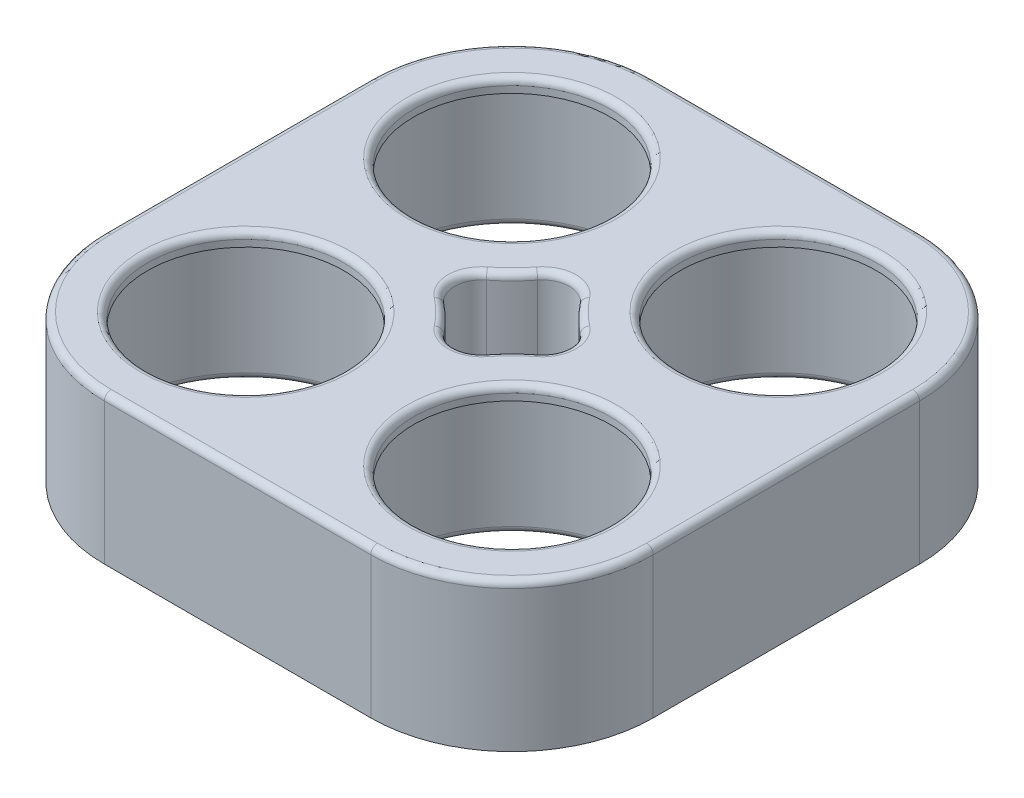
SolidWorks part; units mm, degrees
ref_plane "Front Plane" through (0, 0, 0) normal (0, 0, 1) x (1, 0, 0)
ref_plane "Top Plane" through (0, 0, 0) normal (0, 1, 0) x (1, 0, 0)
ref_plane "Right Plane" through (0, 0, 0) normal (1, 0, 0) x (0, 0, -1)
sketch "Esquisse1" plane through (0, 0, 0) normal (0, 1, 0) x (1, 0, 0)
  line L0 (0, 0) -> (19.8, 0) construction
  line L1 (0, 0) -> (0, 19.8) construction
  line L2 (19.8, 0) -> (19.8, 19.8) construction
  line L3 (-10.5, 19.8) -> (-10.5, 0)
  line L4 (0, 30.3) -> (19.8, 30.3)
  line L5 (30.3, 19.8) -> (30.3, 0)
  line L6 (0, -10.5) -> (19.8, -10.5)
  circle A0 centre (0, 0) radius 9.3
  arc A1 (-10.5, 0) -> (0, -10.5) centre (0, 0) ccw
  circle A2 centre (0, 19.8) radius 9.3
  arc A3 (6.4105, 11.484) -> (8.316, 13.3895) centre (0, 19.8) ccw
  circle A4 centre (19.8, 0) radius 9.3
  arc A5 (13.3895, 8.316) -> (11.484, 6.4105) centre (19.8, 0) ccw
  circle A6 centre (19.8, 19.8) radius 9.3
  arc A7 (30.3, 19.8) -> (19.8, 30.3) centre (19.8, 19.8) ccw
  arc A8 (0, 30.3) -> (-10.5, 19.8) centre (0, 19.8) ccw
  arc A9 (11.484, 13.3895) -> (13.3895, 11.484) centre (19.8, 19.8) ccw
  arc A10 (8.316, 6.4105) -> (6.4105, 8.316) centre (0, 0) ccw
  arc A11 (19.8, -10.5) -> (30.3, 0) centre (19.8, 0) ccw
  arc A12 (6.4105, 11.484) -> (6.4105, 8.316) centre (7.6315, 9.9) ccw
  arc A13 (8.316, 13.3895) -> (11.484, 13.3895) centre (9.9, 12.1685) cw
  arc A14 (13.3895, 11.484) -> (13.3895, 8.316) centre (12.1685, 9.9) cw
  arc A15 (8.316, 6.4105) -> (11.484, 6.4105) centre (9.9, 7.6315) ccw
  dimension "D1" = 18.6
  dimension "D2" = 18.6
  dimension "D3" = 18.6
  dimension "D4" = 18.6
  dimension "D5" = 1.2
  dimension "D6" = 1.2
  dimension "D7" = 1.2
  dimension "D8" = 1.2
  dimension "D9" = 2
extrude "Boss.-Extru.1" add sketch "Esquisse1" along normal blind 10
sketch "Esquisse2" plane through (0, 10, 0) normal (0, 1, 0) x (1, 0, 0)
  line L148 (-10.5, 19.8) -> (-10.5, 0)
  line L149 (0, -10.5) -> (19.8, -10.5)
  line L150 (30.3, 0) -> (30.3, 19.8)
  line L151 (19.8, 30.3) -> (0, 30.3)
  line L152 (-10.5, 19.8) -> (-10.5, 0)
  line L153 (0, -10.5) -> (19.8, -10.5)
  line L154 (30.3, 0) -> (30.3, 19.8)
  line L155 (19.8, 30.3) -> (0, 30.3)
  circle A403 centre (0, 19.8) radius 7.3
  circle A404 centre (19.8, 19.8) radius 7.3
  circle A405 centre (19.8, 0) radius 7.3
  circle A406 centre (0, 0) radius 7.3
  arc A407 (-10.5, 0) -> (0, -10.5) centre (0, 0) ccw
  arc A408 (19.8, -10.5) -> (30.3, 0) centre (19.8, 0) ccw
  arc A409 (30.3, 19.8) -> (19.8, 30.3) centre (19.8, 19.8) ccw
  arc A410 (0, 30.3) -> (-10.5, 19.8) centre (0, 19.8) ccw
  arc A411 (-10.5, 0) -> (0, -10.5) centre (0, 0) ccw
  arc A412 (19.8, -10.5) -> (30.3, 0) centre (19.8, 0) ccw
  arc A413 (30.3, 19.8) -> (19.8, 30.3) centre (19.8, 19.8) ccw
  arc A414 (0, 30.3) -> (-10.5, 19.8) centre (0, 19.8) ccw
  circle A415 centre (0, 19.8) radius 9.3 construction
  circle A416 centre (0, 0) radius 9.3 construction
  circle A417 centre (19.8, 0) radius 9.3 construction
  circle A418 centre (19.8, 19.8) radius 9.3 construction
  dimension "D2" = 2
  dimension "D3" = 2
  dimension "D4" = 2
  dimension "D5" = 2
  dimension "D1" = 0
extrude "Boss.-Extru.2" add sketch "Esquisse2" along normal blind 1
sketch "Esquisse3" plane through (0, 10, 0) normal (0, -1, 0) x (1, 0, 0)
  arc A16 (6.4105, -8.316) -> (8.316, -6.4105) centre (0, 0) ccw
  arc A17 (6.4105, -8.316) -> (6.4105, -11.484) centre (7.6315, -9.9) ccw
  arc A18 (8.316, -13.3895) -> (6.4105, -11.484) centre (0, -19.8) ccw
  arc A19 (8.316, -13.3895) -> (11.484, -13.3895) centre (9.9, -12.1685) ccw
  arc A20 (13.3895, -11.484) -> (11.484, -13.3895) centre (19.8, -19.8) ccw
  arc A21 (13.3895, -11.484) -> (13.3895, -8.316) centre (12.1685, -9.9) ccw
  arc A22 (11.484, -6.4105) -> (13.3895, -8.316) centre (19.8, 0) ccw
  arc A23 (11.484, -6.4105) -> (8.316, -6.4105) centre (9.9, -7.6315) ccw
  arc A24 (6.4105, -8.316) -> (8.316, -6.4105) centre (0, 0) ccw
  arc A25 (6.4105, -8.316) -> (6.4105, -11.484) centre (7.6315, -9.9) ccw
  arc A26 (8.316, -13.3895) -> (6.4105, -11.484) centre (0, -19.8) ccw
  arc A27 (8.316, -13.3895) -> (11.484, -13.3895) centre (9.9, -12.1685) ccw
  arc A28 (13.3895, -11.484) -> (11.484, -13.3895) centre (19.8, -19.8) ccw
  arc A29 (13.3895, -11.484) -> (13.3895, -8.316) centre (12.1685, -9.9) ccw
  arc A30 (11.484, -6.4105) -> (13.3895, -8.316) centre (19.8, 0) ccw
  arc A31 (11.484, -6.4105) -> (8.316, -6.4105) centre (9.9, -7.6315) ccw
  dimension "D1" = 0
extrude "Enlèv. mat.-Extru.1" cut sketch "Esquisse3" against normal through all
fillet "Congé1" radius 0.5 32 edges at (7.4246, 0, -12.3754) (9.9, 0, -14.1685) (12.3754, 0, -12.3754) (14.1685, 0, -9.9) (12.3754, 0, -7.4246) (9.9, 0, -5.6315) (7.4246, 0, -7.4246) (14.1685, 11, -9.9) (12.3754, 11, -12.3754) (9.9, 11, -14.1685) (7.4246, 11, -12.3754) (5.6315, 11, -9.9) (7.4246, 11, -7.4246) (9.9, 11, -5.6315) (-7.4246, 11, -27.2246) (9.9, 11, -30.3) (27.2246, 11, -27.2246) (30.3, 11, -9.9) (27.2246, 11, 7.4246) (9.9, 11, 10.5) (-7.4246, 11, 7.4246) (5.6315, 0, -9.9) (19.8, 0, -10.5) (19.8, 0, 9.3) (0, 0, 9.3) (0, 0, -10.5) (12.3754, 11, -7.4246) (0, 11, 7.3) (19.8, 11, 7.3) (19.8, 11, -12.5) (0, 11, -12.5) (-10.5, 11, -9.9)
